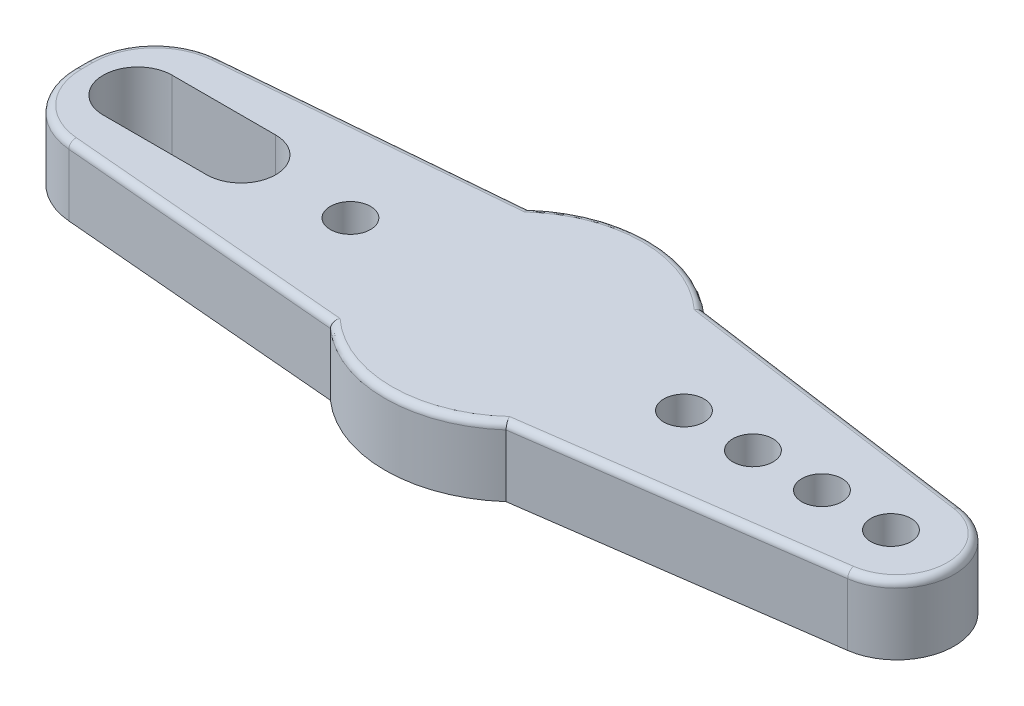
SolidWorks part; units mm, degrees
ref_plane "Front Plane" through (0, 0, 0) normal (0, 0, 1) x (1, 0, 0)
ref_plane "Top Plane" through (0, 0, 0) normal (0, 1, 0) x (1, 0, 0)
ref_plane "Right Plane" through (0, 0, 0) normal (1, 0, 0) x (0, 0, -1)
sketch "Sketch1" plane through (0, 8.7785, 0) normal (0, 1, 0) x (1, 0, 0)
  line L0 (24.4839, -36.0094) -> (39.6665, -34.7094)
  line L1 (24.4839, -42.0094) -> (39.6665, -43.3094)
  line L2 (24.4839, -42.0094) -> (24.4839, -36.0094)
  line L3 (47.3013, -43.3094) -> (60.3305, -41.4852)
  line L4 (47.3013, -34.7094) -> (60.3305, -36.5335)
  line L5 (26.9839, -39.0094) -> (31.4839, -39.0094) construction
  line L6 (26.9839, -37.5094) -> (31.4839, -37.5094)
  line L7 (26.9839, -40.5094) -> (31.4839, -40.5094)
  arc A2 (39.6665, -34.7094) -> (47.3013, -34.7094) centre (43.4839, -39.0094) cw
  arc A3 (39.6665, -43.3094) -> (47.3013, -43.3094) centre (43.4839, -39.0094) ccw
  arc A4 (60.3305, -36.5335) -> (60.3305, -41.4852) centre (59.9839, -39.0094) cw
  arc A6 (60.3305, -41.4852) -> (60.3305, -36.5335) centre (59.9839, -39.0094) ccw construction
  circle A10 centre (36.2339, -39.0094) radius 0.875
  circle A11 centre (50.7339, -39.0094) radius 0.875
  circle A12 centre (53.7339, -39.0094) radius 0.875
  circle A13 centre (56.7339, -39.0094) radius 0.875
  circle A14 centre (59.7339, -39.0094) radius 0.875
  circle A15 centre (43.4839, -39.0094) radius 3.5
  arc A16 (26.9839, -37.5094) -> (26.9839, -40.5094) centre (26.9839, -39.0094) ccw
  arc A17 (31.4839, -40.5094) -> (31.4839, -37.5094) centre (31.4839, -39.0094) ccw
  point P12 (29.2339, -39.0094)
  point P13 (24.4839, -39.0094)
  circle M45 centre (43.4839, -39.0094) radius 4.7
  circle M47 centre (33.2339, -39.0094) radius 0.75
  arc M54 (39.6665, -43.3094) -> (47.3013, -43.3094) centre (43.4839, -39.0094) ccw
  line M55 (47.3013, -43.3094) -> (60.3305, -41.4852)
  arc M56 (60.3305, -41.4852) -> (60.3305, -36.5335) centre (59.9839, -39.0094) ccw
  line M57 (60.3305, -36.5335) -> (47.3013, -34.7094)
  arc M58 (47.3013, -34.7094) -> (39.6665, -34.7094) centre (43.4839, -39.0094) ccw
  line M59 (39.6665, -34.7094) -> (26.6373, -36.5335)
  arc M60 (26.6373, -36.5335) -> (26.6373, -41.4852) centre (26.9839, -39.0094) ccw
  line M61 (26.6373, -41.4852) -> (39.6665, -43.3094)
  dimension "D1" = 1.5
  dimension "D2" = 6
  dimension "D3" = 1.75
  dimension "D4" = 7
  dimension "D5" = 19
  dimension "D6" = 16.5
  dimension "D7" = 12
extrude "Boss-Extrude1" add sketch "Sketch1" along normal blind 3 contours L2 A17 L7 A16 L6 A14 A13 A12 A11 A10 M60 M61 M54 M55 M56 M57 M58 M59 M47 M45 | A15 M45 | L2 L1 M61 M60 | L2 L0 M60 M59 | A17 M47
sketch "Sketch2" plane through (0, 11.7785, 0) normal (0, 1, 0) x (1, 0, 0)
  circle A0 centre (43.4839, -39.0094) radius 3.5
  circle M35 centre (43.4839, -39.0094) radius 3.5
  dimension "D1" = 7
extrude "Boss-Extrude2" add sketch "Sketch2" against normal offset from surface (2 mm away) 1 contours M35 up to face at (43.2147, 8.7785, 39.0094)
fillet "Fillet1" radius 3 2 edges at (24.4839, 10.2785, 36.0094) (24.4839, 10.2785, 42.0094)
fillet "Fillet2" radius 0.3 10 edges at (53.8159, 11.7785, 35.6215) (62.4839, 11.7785, 39.0094) (33.4472, 11.7785, 35.2419) (25.274, 11.7785, 36.7347) (24.4839, 11.7785, 39.0094) (25.274, 11.7785, 41.2841) (43.4839, 11.7785, 33.2594) (53.8159, 11.7785, 42.3973) (33.4472, 11.7785, 42.7769) (43.4839, 11.7785, 44.7594)
